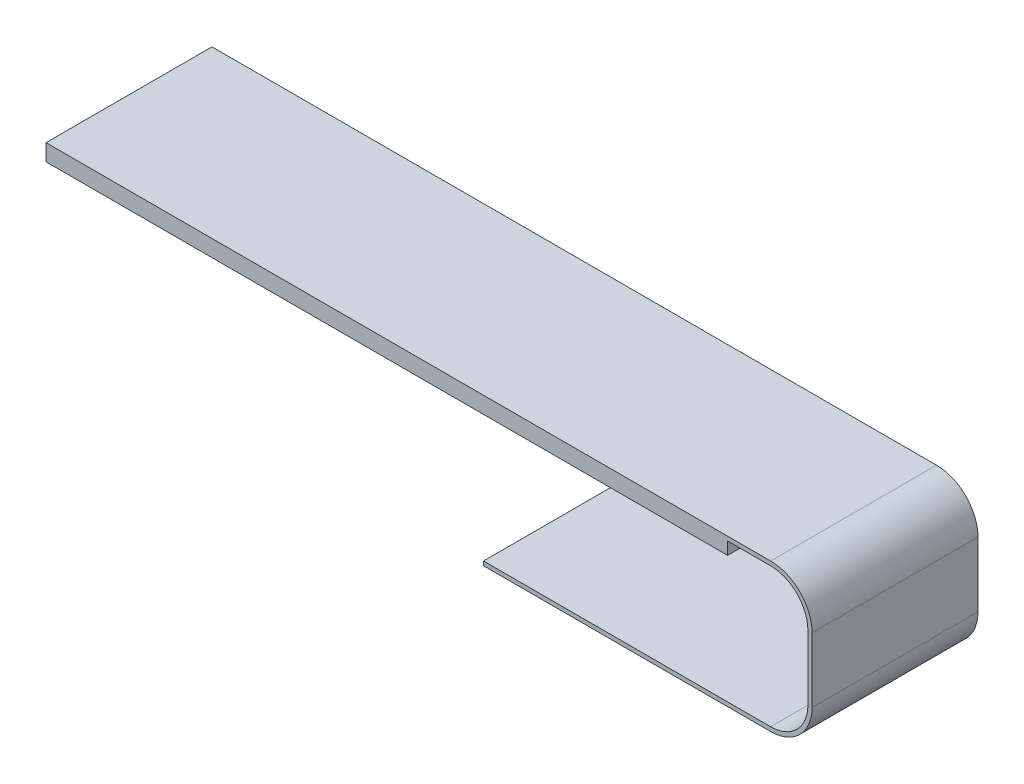
SolidWorks part; units mm, degrees
ref_plane "前视基准面" through (0, 0, 0) normal (0, 0, 1) x (1, 0, 0)
ref_plane "上视基准面" through (0, 0, 0) normal (0, 1, 0) x (1, 0, 0)
ref_plane "右视基准面" through (0, 0, 0) normal (1, 0, 0) x (0, 0, -1)
sketch "草图1" plane through (0, 0, 0) normal (0, 0, 1) x (1, 0, 0)
  line L0 (0, 0) -> (17.465, 0)
  line L1 (0, 0.1) -> (17.465, 0.1)
  line L2 (17.465, -3.36) -> (10.545, -3.36)
  line L3 (17.465, -3.46) -> (10.545, -3.46)
  line L4 (0, 0) -> (0, 0.1)
  line L5 (10.545, -3.36) -> (10.545, -3.46)
  line L6 (17.465, 0.1995) -> (17.465, -3.5505) construction
  line L7 (17.465, -0.9) -> (17.465, -2.46) construction
  line L8 (18.465, -0.9) -> (18.465, -2.46) construction
  line L9 (16.465, -0.9) -> (16.465, -2.46) construction
  line L10 (15.238, 0.1) -> (15.238, -3.46) construction
  line L11 (15.238, -1.68) -> (17.465, -1.68) construction
  line L12 (18.365, -0.9) -> (18.365, -2.46) construction
  line L13 (16.565, -0.9) -> (16.565, -2.46) construction
  line L14 (18.465, -0.9) -> (18.465, -2.46)
  line L16 (18.365, -0.9) -> (18.365, -2.46)
  arc A2 (17.465, -3.46) -> (17.465, 0.1) centre (17.465, -1.68) ccw construction
  arc A3 (17.465, -3.36) -> (17.465, 0) centre (17.465, -1.68) ccw construction
  arc A4 (18.465, -0.9) -> (16.465, -0.9) centre (17.465, -0.9) ccw construction
  arc A5 (16.465, -2.46) -> (18.465, -2.46) centre (17.465, -2.46) ccw construction
  arc A6 (16.565, -2.46) -> (18.365, -2.46) centre (17.465, -2.46) ccw construction
  arc A7 (18.365, -0.9) -> (16.565, -0.9) centre (17.465, -0.9) ccw construction
  arc A8 (17.465, 0.1) -> (18.465, -0.9) centre (17.465, -0.9) cw
  arc A9 (17.465, 0) -> (18.365, -0.9) centre (17.465, -0.9) cw
  arc A10 (17.465, -3.36) -> (18.365, -2.46) centre (17.465, -2.46) ccw
  arc A11 (17.465, -3.46) -> (18.465, -2.46) centre (17.465, -2.46) ccw
  point P15 (17.465, -1.68)
  dimension "D1" = 17.465
  dimension "D2" = 3.36
  dimension "D4" = 6.92
  dimension "D6" = 1
  dimension "D3" = 0.1
  dimension "D5" = 0.1
extrude "凸台-拉伸1" add sketch "草图1" along normal blind 4
sketch "草图2" plane through (0, 0, 0) normal (0, -1, 0) x (1, 0, 0)
  line L0 (0, 0) -> (17.465, 0) construction
  line L1 (0, 4) -> (16.43, 4)
  line L2 (0, 4) -> (0, 0)
  line L3 (0, 0) -> (16.43, 0)
  line L4 (16.43, 4) -> (16.43, 0)
  line L6 (17.465, 4) -> (17.465, 0) construction
  dimension "D1" = 1.035
extrude "凸台-拉伸2" add sketch "草图2" along normal blind 0.3
sketch "草图6" plane through (0, -3.46, 0) normal (0, -1, 0) x (1, 0, 0)
  line L0 (1.0518, 0) -> (20.2618, 0) construction
sketch "草图5" plane through (0, -3.46, 0) normal (0, -1, 0) x (1, 0, 0)
  line L0 (10.545, 4) -> (10.545, 0) construction
  line L1 (10.545, 3.679) -> (12.1714, 3.679)
  line L2 (10.545, 3.679) -> (10.545, 3.111)
  line L3 (10.545, 3.111) -> (12.1714, 3.111)
  line L4 (12.1714, 3.679) -> (12.1714, 3.111)
  line L5 (10.545, 2.749) -> (10.545, 2.181)
  line L6 (10.545, 2.749) -> (12.1714, 2.749)
  line L7 (12.1714, 2.749) -> (12.1714, 2.181)
  line L8 (10.545, 2.181) -> (12.1714, 2.181)
  line L9 (10.545, 1.819) -> (10.545, 1.251)
  line L10 (10.545, 1.819) -> (12.1714, 1.819)
  line L11 (12.1714, 1.819) -> (12.1714, 1.251)
  line L12 (10.545, 1.251) -> (12.1714, 1.251)
  line L13 (10.545, 0.889) -> (10.545, 0.321)
  line L14 (10.545, 0.889) -> (12.1714, 0.889)
  line L15 (12.1714, 0.889) -> (12.1714, 0.321)
  line L16 (10.545, 0.321) -> (12.1714, 0.321)
  line L17 (12.1714, 3.679) -> (12.1714, 0.321) construction
  line L18 (12.1714, 2) -> (16.985, 2) construction
  dimension "D1" = 0.568
  dimension "D2" = 4
  dimension "D3" = 1.6264
extrude "切除-拉伸1" cut sketch "草图5" against normal blind 0.02
